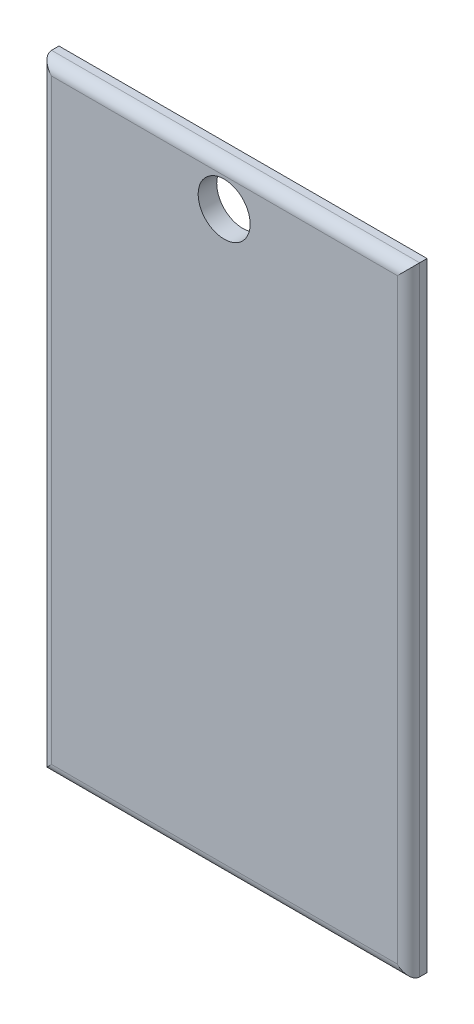
SolidWorks part; units mm, degrees
ref_plane "Plano frontal" through (0, 0, 0) normal (0, 0, 1) x (1, 0, 0)
ref_plane "Plano superior" through (0, 0, 0) normal (0, 1, 0) x (1, 0, 0)
ref_plane "Plano direito" through (0, 0, 0) normal (1, 0, 0) x (0, 0, -1)
sketch "Esboço1" plane through (0, 0, 0) normal (0, 0, 1) x (1, 0, 0)
  line L1 (-44.0525, 94.6578) -> (55.0475, 94.6578)
  line L2 (-44.0525, 94.6578) -> (-44.0525, -71.8622)
  line L3 (-44.0525, -71.8622) -> (55.0475, -71.8622)
  line L4 (55.0475, 94.6578) -> (55.0475, -71.8622)
extrude "Ressalto-extrusão1" add sketch "Esboço1" along normal blind 5
fillet "Filete1" radius 3 4 edges at (5.4975, -71.8622, 5) (55.0475, 11.3978, 5) (5.4975, 94.6578, 5) (-44.0525, 11.3978, 5)
sketch "Esboço2" plane through (0, 0, 0) normal (0, 0, -1) x (-1, 0, 0)
  line L0 (-55.0475, 94.6578) -> (44.0525, 94.6578) construction
  line L2 (-55.0475, -71.8622) -> (-55.0475, 94.6578) construction
  circle A0 centre (-51.4975, 91.1078) radius 3.1
  dimension "D1" = 3.55
  dimension "D2" = 3.55
extrude "Corte-extrusão1" cut sketch "Esboço2" against normal blind 1.6
sketch "Esboço3" plane through (0, 0, 0) normal (0, 0, -1) x (-1, 0, 0)
  line L0 (44.0525, 94.6578) -> (44.0525, -71.8622) construction
  line L1 (-55.0475, 94.6578) -> (44.0525, 94.6578) construction
  circle A0 centre (40.5025, 91.1078) radius 3.1
  dimension "D1" = 3.55
  dimension "D2" = 3.55
extrude "Corte-extrusão2" cut sketch "Esboço3" against normal blind 1.6
sketch "Esboço4" plane through (0, 0, 0) normal (0, 0, -1) x (-1, 0, 0)
  line L0 (44.0525, -71.8622) -> (-55.0475, -71.8622) construction
  line L1 (-55.0475, -71.8622) -> (-55.0475, 94.6578) construction
  circle A0 centre (-51.4975, -68.3122) radius 3.1
  dimension "D1" = 3.55
  dimension "D2" = 3.55
extrude "Corte-extrusão3" cut sketch "Esboço4" against normal blind 1.6
sketch "Esboço5" plane through (0, 0, 0) normal (0, 0, -1) x (-1, 0, 0)
  line L0 (44.0525, 94.6578) -> (44.0525, -71.8622) construction
  line L1 (44.0525, -71.8622) -> (-55.0475, -71.8622) construction
  circle A0 centre (40.5025, -68.3122) radius 3.1
  dimension "D1" = 3.55
  dimension "D2" = 3.55
extrude "Corte-extrusão4" cut sketch "Esboço5" against normal blind 1.6 contours A0
sketch "Esboço6" plane through (0, 0, 0) normal (0, 0, -1) x (-1, 0, 0)
  line L0 (-52.0475, 91.6578) -> (41.0525, 91.6578) construction
  circle A0 centre (-5.4187, 83.8578) radius 7
  circle A1 centre (40.5025, 91.1078) radius 3.1 construction
  point P4 (-5.3895, 83.6753)
  dimension "D1" = 46.49
  dimension "D2" = 7.8
extrude "Corte-extrusão5" cut sketch "Esboço6" against normal blind 10
